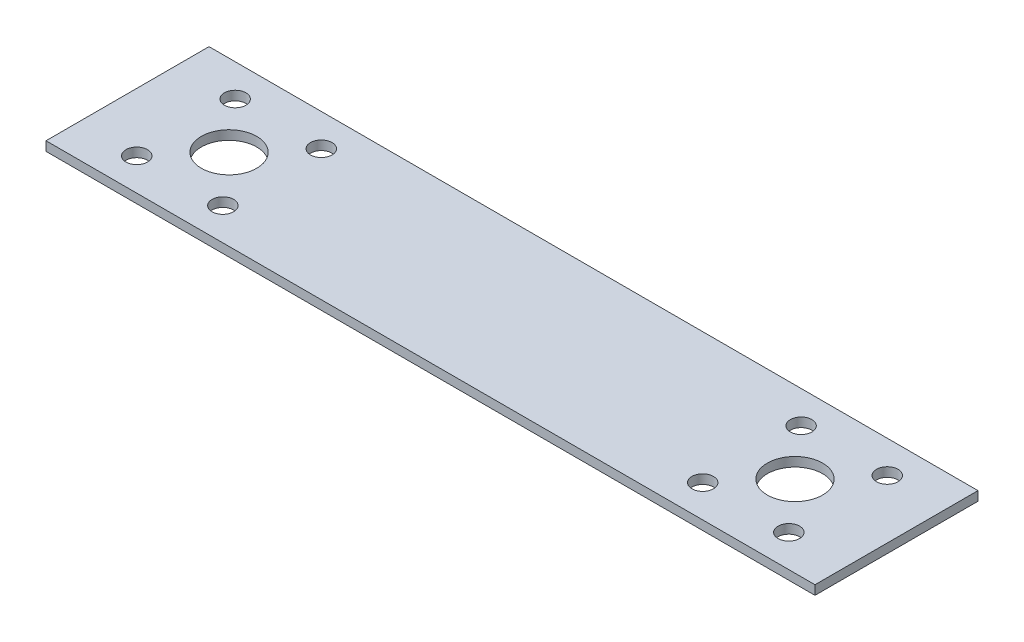
SolidWorks part; units mm, degrees
ref_plane "Front Plane" through (0, 0, 0) normal (0, 0, 1) x (1, 0, 0)
ref_plane "Top Plane" through (0, 0, 0) normal (0, 1, 0) x (1, 0, 0)
ref_plane "Right Plane" through (0, 0, 0) normal (1, 0, 0) x (0, 0, -1)
sketch "Sketch4" plane through (0, 0, 0) normal (0, 1, 0) x (1, 0, 0)
  line L0 (-63.159, 50.9083) -> (-30.159, 50.9083)
  line L2 (-63.159, 50.9083) -> (61.841, 50.9083)
  line L9 (-30.159, 24.4083) -> (-63.159, 24.4083)
  line L11 (-63.159, 24.4083) -> (-63.159, 50.9083)
  line L12 (61.841, 50.9083) -> (28.841, 50.9083)
  line L14 (28.841, 24.4083) -> (61.841, 24.4083)
  line L15 (61.841, 24.4083) -> (61.841, 50.9083)
  line L16 (-63.159, 24.4083) -> (61.841, 24.4083)
  circle A0 centre (-46.659, 37.6583) radius 4.5
  circle A1 centre (-39.659, 45.6583) radius 1.75
  circle A2 centre (-39.659, 29.6583) radius 1.75
  circle A3 centre (-53.659, 29.6583) radius 1.75
  circle A4 centre (-53.659, 45.6583) radius 1.75
  circle A5 centre (45.341, 37.6583) radius 4.5
  circle A6 centre (52.341, 45.6583) radius 1.75
  circle A7 centre (52.341, 29.6583) radius 1.75
  circle A8 centre (38.341, 45.6583) radius 1.75
  circle A9 centre (38.341, 29.6583) radius 1.75
  dimension "D5" = 9
  dimension "D6" = 3.5
  dimension "D9" = 9
  dimension "D10" = 3.5
  dimension "D2" = 125
  dimension "D3" = 26.5
  dimension "D4" = 33
  dimension "D7" = 16
  dimension "D8" = 14
  dimension "D11" = 16
  dimension "D12" = 14
  dimension "D13" = 26.5
  dimension "D14" = 33
extrude "Boss-Extrude1" add sketch "Sketch4" along normal blind 1.5 contours L9 L16 L14 L15 L2 L0 L11 A9 A8 A7 A6 A5 A4 A3 A2 A1 A0
